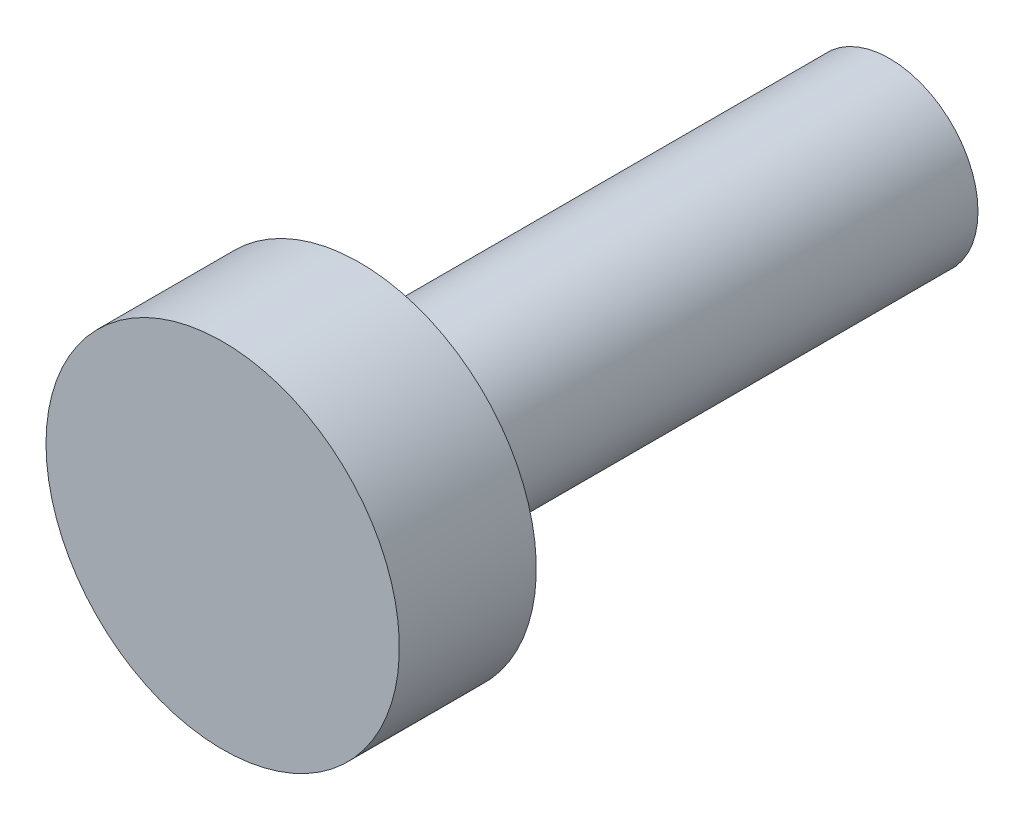
SolidWorks part; units mm, degrees
ref_plane "Plan de face" through (0, 0, 0) normal (0, 0, 1) x (1, 0, 0)
ref_plane "Plan de dessus" through (0, 0, 0) normal (0, 1, 0) x (1, 0, 0)
ref_plane "Plan de droite" through (0, 0, 0) normal (1, 0, 0) x (0, 0, -1)
sketch "Esquisse1" plane through (0, 0, 0) normal (0, 0, 1) x (1, 0, 0)
  circle A0 centre (0, 0) radius 4
  dimension "D1" = 8
extrude "Boss.-Extru.1" add sketch "Esquisse1" along normal blind 3.1
sketch "Esquisse2" plane through (0, 0, 0) normal (0, 0, -1) x (-1, 0, 0)
  circle A0 centre (0, 0) radius 2
  dimension "D1" = 4
extrude "Boss.-Extru.2" add sketch "Esquisse2" along normal blind 12
